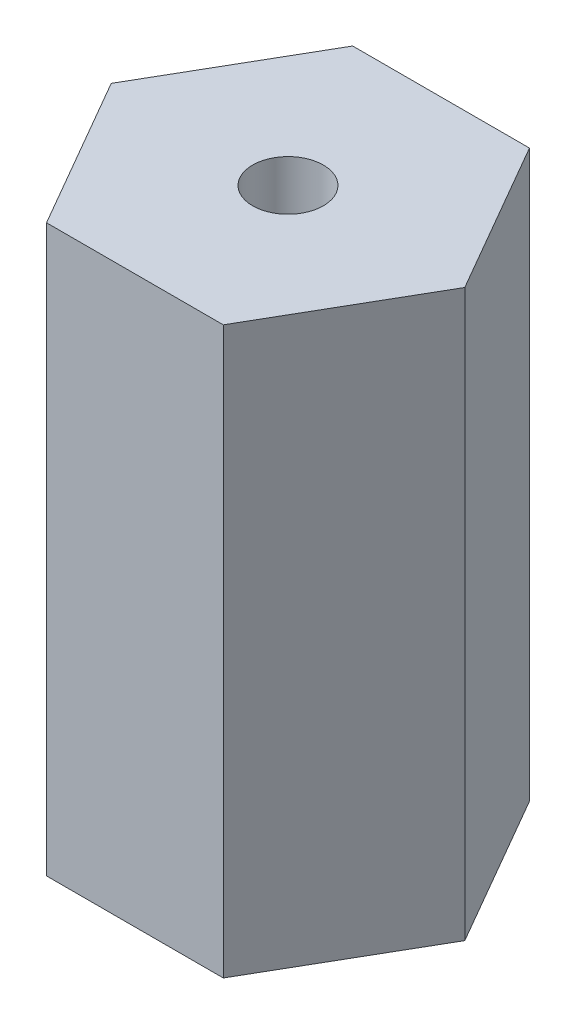
SolidWorks part; units mm, degrees
ref_plane "Front Plane" through (0, 0, 0) normal (0, 0, 1) x (1, 0, 0)
ref_plane "Top Plane" through (0, 0, 0) normal (0, 1, 0) x (1, 0, 0)
ref_plane "Right Plane" through (0, 0, 0) normal (1, 0, 0) x (0, 0, -1)
sketch "Sketch1" plane through (0, 0, 0) normal (0, 1, 0) x (1, 0, 0)
  line L1 (5, 0) -> (2.5, 4.3301)
  line L2 (2.5, 4.3301) -> (-2.5, 4.3301)
  line L3 (-2.5, 4.3301) -> (-5, 0)
  line L4 (-5, 0) -> (-2.5, -4.3301)
  line L5 (-2.5, -4.3301) -> (2.5, -4.3301)
  line L6 (2.5, -4.3301) -> (5, 0)
  circle A0 centre (0, 0) radius 4.3301 construction
  circle A1 centre (0, 0) radius 1
extrude "Boss-Extrude2" add sketch "Sketch1" along normal blind 16
